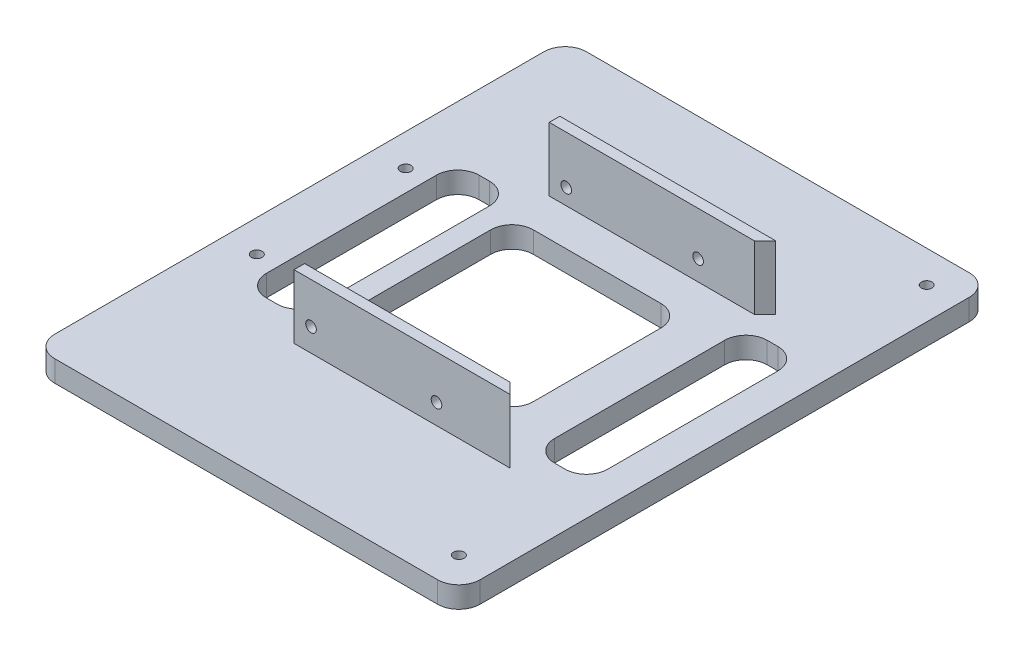
SolidWorks part; units mm, degrees
ref_plane "Plano frontal" through (0, 0, 0) normal (0, 0, 1) x (1, 0, 0)
ref_plane "Plano superior" through (0, 0, 0) normal (0, 1, 0) x (1, 0, 0)
ref_plane "Plano direito" through (0, 0, 0) normal (1, 0, 0) x (0, 0, -1)
sketch "Esboço1" plane through (0, 0, 0) normal (0, 1, 0) x (1, 0, 0)
  line L1 (-88.2759, -57.7155) -> (91.7241, -57.7155)
  line L2 (-98.2759, -47.7155) -> (-98.2759, 182.2845)
  line L3 (-88.2759, 192.2845) -> (91.7241, 192.2845)
  line L4 (101.7241, -47.7155) -> (101.7241, 182.2845)
  arc A0 (-88.2759, -57.7155) -> (-98.2759, -47.7155) centre (-88.2759, -47.7155) cw
  arc A1 (-88.2759, 192.2845) -> (-98.2759, 182.2845) centre (-88.2759, 182.2845) ccw
  arc A2 (101.7241, 182.2845) -> (91.7241, 192.2845) centre (91.7241, 182.2845) ccw
  arc A3 (91.7241, -57.7155) -> (101.7241, -47.7155) centre (91.7241, -47.7155) ccw
  point P6 (-98.2759, -57.7155)
  point P9 (-98.2759, 192.2845)
  point P12 (101.7241, 192.2845)
  dimension "D3" = 10
  dimension "D1" = 200
  dimension "D2" = 250
extrude "Ressalto-extrusão1" add sketch "Esboço1" along normal blind 10
sketch "Esboço2" plane through (0, 10, 0) normal (0, 1, 0) x (1, 0, 0)
  line L0 (91.7241, 192.2845) -> (-88.2759, 192.2845) construction
  line L1 (-98.2759, 182.2845) -> (-98.2759, -47.7155) construction
  line L2 (-98.2759, 67.2845) -> (101.7241, 67.2845) construction
  line L3 (101.7241, -47.7155) -> (101.7241, 182.2845) construction
  line L4 (1.7241, 192.2845) -> (1.7241, -57.7155) construction
  line L5 (-88.2759, -57.7155) -> (91.7241, -57.7155) construction
  line L6 (-98.2759, 67.2845) -> (-98.2759, 87.2845) construction
  line L7 (31.7241, 107.2845) -> (-28.2759, 107.2845)
  line L8 (41.7241, 97.2845) -> (41.7241, 37.2845)
  line L9 (31.7241, 27.2845) -> (-28.2759, 27.2845)
  line L10 (-38.2759, 97.2845) -> (-38.2759, 37.2845)
  line L11 (41.7241, 107.2845) -> (-38.2759, 27.2845) construction
  line L12 (41.7241, 27.2845) -> (-38.2759, 107.2845) construction
  line L13 (-98.2759, 182.2845) -> (-98.2759, -47.7155) construction
  line L14 (-98.2759, 47.2845) -> (-83.2759, 47.2845) construction
  line L15 (-83.2759, 47.2845) -> (-83.2759, 32.2845) construction
  line L16 (-98.2759, 87.2845) -> (-83.2759, 87.2845) construction
  line L17 (-83.2759, 87.2845) -> (-83.2759, 102.2845) construction
  circle A0 centre (-83.2759, 102.2845) radius 2.5
  circle A1 centre (86.7241, 177.2845) radius 2.5
  circle A2 centre (86.7241, -42.7155) radius 2.5
  circle A3 centre (-83.2759, 32.2845) radius 2.5
  arc A4 (41.7241, 97.2845) -> (31.7241, 107.2845) centre (31.7241, 97.2845) ccw
  arc A5 (-38.2759, 97.2845) -> (-28.2759, 107.2845) centre (-28.2759, 97.2845) cw
  arc A6 (-38.2759, 37.2845) -> (-28.2759, 27.2845) centre (-28.2759, 37.2845) ccw
  arc A7 (31.7241, 27.2845) -> (41.7241, 37.2845) centre (31.7241, 37.2845) ccw
  point P20 (1.7241, 67.2845)
  dimension "D1" = 15
  dimension "D2" = 10
  dimension "D4" = 80
  dimension "D5" = 80
extrude "Corte-extrusão1" cut sketch "Esboço2" against normal through all
sketch "Esboço4" plane through (0, 10, 0) normal (0, 1, 0) x (1, 0, 0)
  line L0 (-38.2759, 124.7845) -> (-38.2759, 9.7845) construction
  line L1 (58.2241, 9.7845) -> (-38.2759, 9.7845)
  line L3 (58.2241, 124.7845) -> (-38.2759, 124.7845)
  line L5 (91.7241, 192.2845) -> (-88.2759, 192.2845) construction
  line L7 (58.2241, 9.7845) -> (63.2241, 4.7845)
  line L8 (63.2241, 4.7845) -> (-38.2759, 4.7845)
  line L10 (63.2241, 129.7845) -> (-38.2759, 129.7845)
  line L12 (58.2241, 124.7845) -> (63.2241, 129.7845)
  line L14 (-38.2759, 4.7845) -> (-38.2759, 9.7845)
  line L15 (-59.7759, 4.7845) -> (-59.7759, 129.7845) construction
  line L16 (-54.7759, 9.7845) -> (-54.7759, 124.7845) construction
  line L17 (63.2241, 4.7845) -> (63.2241, 129.7845) construction
  line L18 (58.2241, 9.7845) -> (58.2241, 124.7845) construction
  line L19 (63.2241, 4.7845) -> (-59.7759, 4.7845) construction
  line L20 (58.2241, 9.7845) -> (-54.7759, 9.7845) construction
  line L21 (-38.2759, 124.7845) -> (-38.2759, 129.7845)
  line L22 (58.2241, 124.7845) -> (-54.7759, 124.7845) construction
  line L23 (63.2241, 129.7845) -> (-59.7759, 129.7845) construction
  dimension "D5" = 62.5
  dimension "D3" = 5
extrude "Ressalto-extrusão2" add sketch "Esboço4" along normal blind 30
sketch "Esboço5" plane through (0, 0, -4.7845) normal (0, 0, 1) x (1, 0, 0)
  line L2 (-30.2759, 20.8362) -> (-30.2759, 10.3362) construction
  line L3 (63.2241, 19.5) -> (28.7241, 19.5) construction
  line L4 (63.2241, 40) -> (63.2241, 10) construction
  line L5 (28.7241, 19.5) -> (28.7241, 10) construction
  line L6 (-38.2759, 10) -> (63.2241, 10) construction
  circle A0 centre (-30.2759, 20.8362) radius 2.5
  circle A1 centre (28.7241, 19.5) radius 2.5
  dimension "D3" = 9.5
  dimension "D2" = 10.5
extrude "Corte-extrusão2" cut sketch "Esboço5" against normal blind 5
sketch "Esboço6" plane through (0, 0, -129.7845) normal (0, 0, -1) x (-1, 0, 0)
  line L0 (-31.7241, 10) -> (-31.7241, 19.5) construction
  line L1 (-63.2241, 10) -> (38.2759, 10) construction
  line L2 (-31.7241, 19.5) -> (-63.2241, 19.5) construction
  line L3 (-63.2241, 40) -> (-63.2241, 10) construction
  line L4 (30.2759, 10) -> (30.2759, 17.5) construction
  circle A0 centre (-31.7241, 19.5) radius 2.5
  circle A1 centre (30.2759, 17.5) radius 2.5
  dimension "D3" = 9.5
  dimension "D1" = 31.5
  dimension "D4" = 7.5
extrude "Corte-extrusão3" cut sketch "Esboço6" against normal blind 5
sketch "Esboço7" plane through (0, 10, 0) normal (0, 1, 0) x (1, 0, 0)
  line L0 (86.7241, 67.2845) -> (101.7241, 67.2845) construction
  line L1 (76.7241, 117.2845) -> (71.7241, 117.2845)
  line L2 (86.7241, 107.2845) -> (86.7241, 27.2845)
  line L3 (76.7241, 17.2845) -> (71.7241, 17.2845)
  line L4 (61.7241, 107.2845) -> (61.7241, 27.2845)
  line L5 (101.7241, -47.7155) -> (101.7241, 182.2845) construction
  line L6 (-73.2894, 116.7845) -> (-73.2894, 192.2845) construction
  line L7 (91.7241, 192.2845) -> (-88.2759, 192.2845) construction
  line L9 (-58.2894, 116.7845) -> (-63.2894, 116.7845)
  line L10 (-48.2894, 106.7845) -> (-48.2894, 26.7845)
  line L11 (-58.2894, 16.7845) -> (-63.2894, 16.7845)
  line L12 (-73.2894, 106.7845) -> (-73.2894, 26.7845)
  arc A0 (71.7241, 17.2845) -> (61.7241, 27.2845) centre (71.7241, 27.2845) cw
  arc A1 (76.7241, 17.2845) -> (86.7241, 27.2845) centre (76.7241, 27.2845) ccw
  arc A2 (71.7241, 117.2845) -> (61.7241, 107.2845) centre (71.7241, 107.2845) ccw
  arc A3 (86.7241, 107.2845) -> (76.7241, 117.2845) centre (76.7241, 107.2845) ccw
  arc A4 (-58.2894, 16.7845) -> (-48.2894, 26.7845) centre (-58.2894, 26.7845) ccw
  arc A5 (-73.2894, 26.7845) -> (-63.2894, 16.7845) centre (-63.2894, 26.7845) ccw
  arc A6 (-73.2894, 106.7845) -> (-63.2894, 116.7845) centre (-63.2894, 106.7845) cw
  arc A7 (-48.2894, 106.7845) -> (-58.2894, 116.7845) centre (-58.2894, 106.7845) ccw
  point P12 (61.7241, 17.2845)
  point P15 (86.7241, 17.2845)
  point P20 (86.7241, 117.2845)
  point P28 (-48.2894, 16.7845)
  point P31 (-73.2894, 16.7845)
  dimension "D5" = 10
  dimension "D9" = 10
  dimension "D1" = 15
  dimension "D2" = 75
  dimension "D3" = 100
  dimension "D4" = 25
  dimension "D6" = 25
  dimension "D7" = 100
  dimension "D8" = 75.5
extrude "Corte-extrusão4" cut sketch "Esboço7" against normal blind 10
